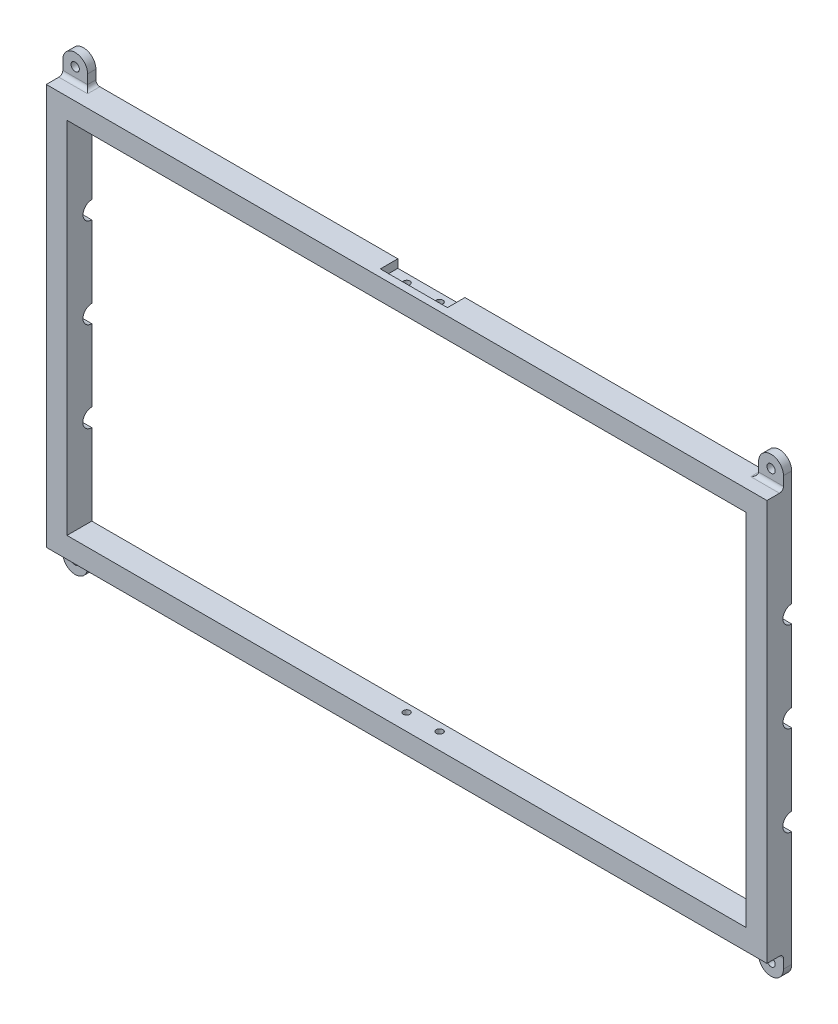
SolidWorks part; units mm, degrees
ref_plane "Front Plane" through (0, 0, 0) normal (0, 0, 1) x (1, 0, 0)
ref_plane "Top Plane" through (0, 0, 0) normal (0, 1, 0) x (1, 0, 0)
ref_plane "Right Plane" through (0, 0, 0) normal (1, 0, 0) x (0, 0, -1)
sketch "Sketch1" plane through (0, 0, 0) normal (0, 0, 1) x (1, 0, 0)
  line L0 (-138.43, 77.0128) -> (138.43, 77.0128)
  line L1 (-130.4798, -69.0626) -> (130.4798, -69.0626)
  line L2 (-130.4798, -69.0626) -> (-130.4798, 69.0626)
  line L3 (-130.4798, 69.0626) -> (130.4798, 69.0626)
  line L4 (130.4798, -69.0626) -> (130.4798, 69.0626)
  line L5 (-130.4798, -69.0626) -> (130.4798, 69.0626) construction
  line L6 (-130.4798, 69.0626) -> (130.4798, -69.0626) construction
  line L7 (138.43, -77.0128) -> (138.43, 77.0128)
  line L8 (-138.43, -77.0128) -> (138.43, -77.0128)
  line L9 (-138.43, -77.0128) -> (-138.43, 77.0128)
  point P0 (0, 0)
  dimension "D1" = 138.1252
  dimension "D2" = 260.9596
  dimension "D3" = 7.9502
extrude "Boss-Extrude1" add sketch "Sketch1" along normal blind 9.525
sketch "Sketch2" plane through (138.43, 0, 0) normal (1, 0, 0) x (0, 0, -1)
  line L0 (0, -77.0128) -> (0, 77.0128) construction
  circle A0 centre (0, 0) radius 3.3655
  circle A1 centre (0, 34.5313) radius 3.3655
  circle A2 centre (0, -34.5313) radius 3.429
  dimension "D1" = 6.731
  dimension "D4" = 6.858
  dimension "D2" = 34.5313
  dimension "D3" = 34.5313
extrude "Cut-Extrude1" cut sketch "Sketch2" against normal through all
sketch "Sketch3" plane through (0, 0, 0) normal (0, 0, -1) x (-1, 0, 0)
  line L0 (-138.43, 77.0128) -> (-138.43, 82.0928)
  line L1 (-128.905, 77.0128) -> (-128.905, 82.0928)
  line L2 (-138.43, 77.0128) -> (138.43, 77.0128) construction
  line L3 (-138.43, 77.0128) -> (-128.905, 77.0128)
  arc A0 (-138.43, 82.0928) -> (-128.905, 82.0928) centre (-133.6675, 82.0928) cw
  circle A1 centre (-133.6675, 82.0928) radius 1.5875
  point P7 (-138.43, 79.5528)
  dimension "D3" = 3.175
  dimension "D1" = 5.08
  dimension "D2" = 9.525
extrude "Boss-Extrude2" add sketch "Sketch3" against normal blind 3.175
mirror "Mirror1" about plane through (0, 0, 0) normal (1, 0, 0) of "Boss-Extrude2"
mirror "Mirror2" about plane through (0, 0, 0) normal (0, 1, 0) of "Mirror1", "Boss-Extrude2"
fillet "Fillet1" radius 1.524 8 edges at (128.905, 77.0128, 1.5875) (-128.905, 77.0128, 1.5875) (-128.905, -77.0128, 1.5875) (-133.6675, -77.0128, 3.175) (128.905, -77.0128, 1.5875) (133.6675, -77.0128, 3.175) (133.6675, 77.0128, 3.175) (-133.6675, 77.0128, 3.175)
sketch "Sketch4" plane through (0, 77.0128, 0) normal (0, 1, 0) x (1, 0, 0)
  line L0 (127.381, 0) -> (-127.381, 0) construction
  line L1 (-12.8905, -6.731) -> (12.8905, -6.731)
  line L2 (-12.8905, -6.731) -> (-12.8905, 6.731)
  line L3 (-12.8905, 6.731) -> (12.8905, 6.731)
  line L4 (12.8905, -6.731) -> (12.8905, 6.731)
  line L5 (-12.8905, -6.731) -> (12.8905, 6.731) construction
  line L6 (-12.8905, 6.731) -> (12.8905, -6.731) construction
  point P0 (0, 0)
  dimension "D1" = 25.781
  dimension "D2" = 6.731
extrude "Cut-Extrude2" cut sketch "Sketch4" against normal blind 3.175
sketch "Sketch5" plane through (0, 73.8378, 0) normal (0, 1, 0) x (1, 0, 0)
  circle A0 centre (6.35, -3.175) radius 1.27
  circle A1 centre (-6.35, -3.175) radius 1.27
  point P4 (0, 0)
  point P6 (0, 0)
  dimension "D3" = 2.54
  dimension "D1" = 6.35
  dimension "D2" = 3.175
  dimension "D4" = 6.35
  dimension "D5" = 3.175
extrude "Cut-Extrude3" cut sketch "Sketch5" against normal up to next
mirror "Mirror3" about plane through (0, 0, 0) normal (0, 1, 0) of "Cut-Extrude2", "Cut-Extrude3"
